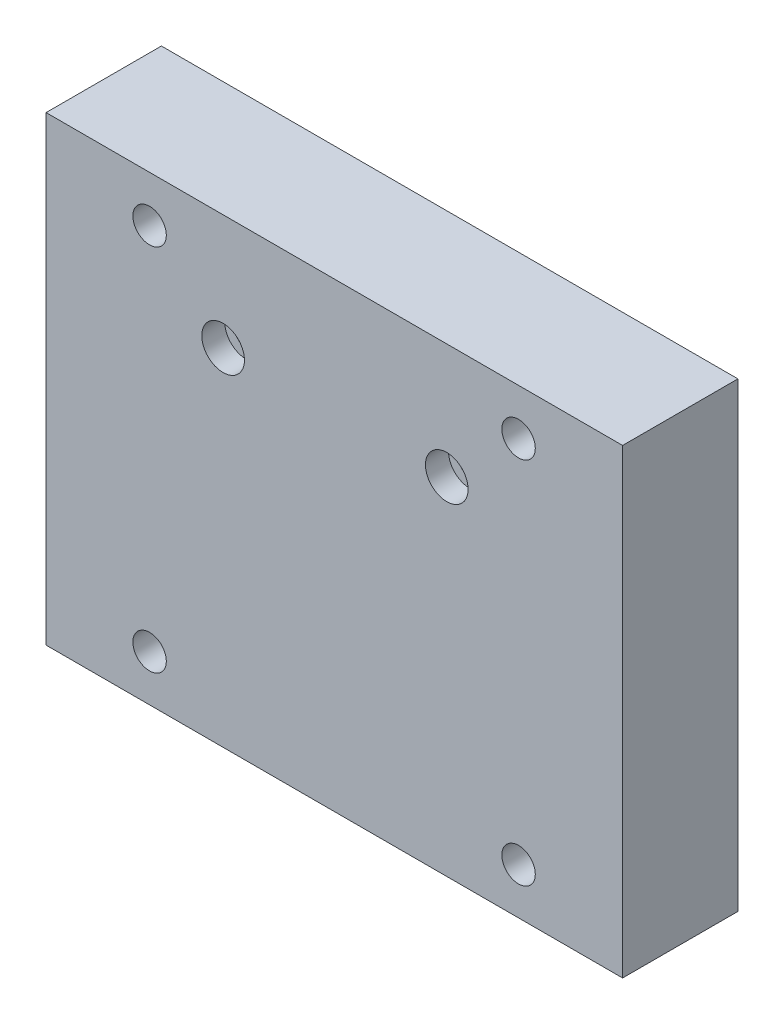
SolidWorks part; units mm, degrees
ref_plane "前视基准面" through (0, 0, 0) normal (0, 0, 1) x (1, 0, 0)
ref_plane "上视基准面" through (0, 0, 0) normal (0, 1, 0) x (1, 0, 0)
ref_plane "右视基准面" through (0, 0, 0) normal (1, 0, 0) x (0, 0, -1)
sketch "草图1" plane through (0, 0, 0) normal (0, 0, 1) x (1, 0, 0)
  line L1 (-25, -20) -> (25, -20)
  line L2 (-25, -20) -> (-25, 20)
  line L3 (-25, 20) -> (25, 20)
  line L4 (25, -20) -> (25, 20)
  line L5 (-25, -20) -> (25, 20) construction
  line L6 (-25, 20) -> (25, -20) construction
  point P0 (0, 0)
  dimension "D1" = 50
  dimension "D2" = 40
extrude "凸台-拉伸1" add sketch "草图1" along normal blind 10
sketch "草图2" plane through (0, 0, 10) normal (0, 0, 1) x (1, 0, 0)
  line L0 (-14.6038, 10) -> (14.944, 10) construction
  line L2 (25, 20) -> (-25, 20) construction
  circle A0 centre (-9.6483, 10) radius 1
  circle A1 centre (9.7517, 10) radius 1
  dimension "D1" = 2
  dimension "D2" = 2
  dimension "D3" = 19.4
  dimension "D5" = 10
extrude "切除-拉伸1" cut sketch "草图2" against normal through all
sketch "草图10" plane through (0, 0, 10) normal (0, 0, 1) x (1, 0, 0)
  circle A0 centre (-9.6483, 10) radius 1.85
  circle A1 centre (9.7517, 10) radius 1.85
  dimension "D1" = 3.7
  dimension "D2" = 3.7
extrude "切除-拉伸6" cut sketch "草图10" against normal blind 2
sketch "草图11" plane through (0, 0, 0) normal (0, 0, -1) x (-1, 0, 0)
  line L5 (-25, 20) -> (25, 20) construction
  line L6 (-13, 7) -> (13, 7)
  line L8 (0, 0) -> (0, -13.6676) construction
  line L9 (-13, 7) -> (-13, 13)
  line L10 (-13, 13) -> (13, 13)
  line L11 (13, 7) -> (13, 13)
  line L12 (-13, 7) -> (13, 13) construction
  line L13 (-13, 13) -> (13, 7) construction
  point P0 (0, 0)
  point P1 (0, 10)
  dimension "D1" = 26
  dimension "D2" = 6
  dimension "D3" = 7
extrude "切除-拉伸7" cut sketch "草图11" against normal blind 6.3
sketch "草图13" plane through (0, 0, 10) normal (0, 0, 1) x (1, 0, 0)
  line L0 (-16.0235, 16) -> (15.9765, 16) construction
  line L1 (15.9765, 16) -> (15.9765, -16) construction
  line L2 (15.9765, -16) -> (-16.0235, -16) construction
  line L3 (-16.0235, -16) -> (-16.0235, 16) construction
  line L4 (25, 20) -> (-25, 20) construction
  line L5 (-25, -20) -> (25, -20) construction
  circle A0 centre (-16.0235, 16) radius 1.45
  circle A1 centre (-16.0235, -16) radius 1.45
  circle A2 centre (15.9765, 16) radius 1.45
  circle A3 centre (15.9765, -16) radius 1.45
  dimension "D1" = 4
  dimension "D3" = 2.9
  dimension "D4" = 2.9
  dimension "D5" = 2.9
  dimension "D6" = 2.9
  dimension "D2" = 4
  dimension "D7" = 32
extrude "切除-拉伸8" cut sketch "草图13" against normal blind 10
